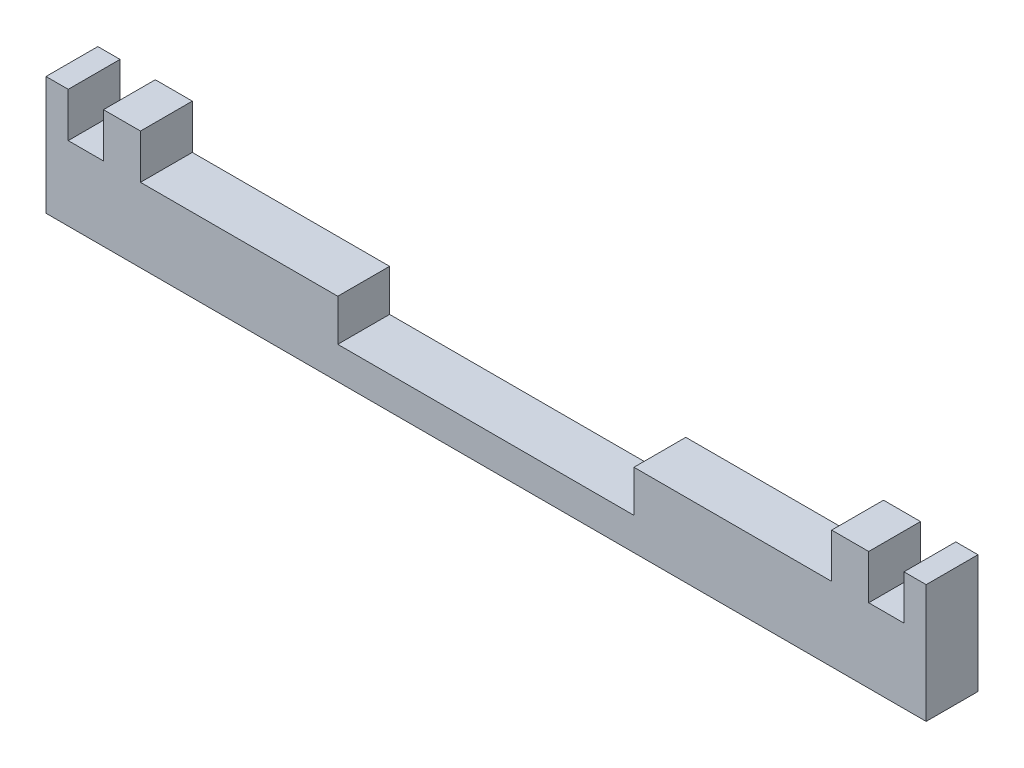
SolidWorks part; units mm, degrees
ref_plane "Front Plane" through (0, 0, 0) normal (0, 0, 1) x (1, 0, 0)
ref_plane "Top Plane" through (0, 0, 0) normal (0, 1, 0) x (1, 0, 0)
ref_plane "Right Plane" through (0, 0, 0) normal (1, 0, 0) x (0, 0, -1)
sketch "Sketch1" plane through (0, 0, 0) normal (0, 0, 1) x (1, 0, 0)
  line L8 (-95.4472, -23.6971) -> (55.505, -23.6971)
  line L9 (55.505, -23.6971) -> (55.505, -3.3771)
  line L10 (55.505, -3.3771) -> (51.695, -3.3771)
  line L11 (51.695, -3.3771) -> (51.695, -10.9971)
  line L12 (51.695, -10.9971) -> (45.6498, -10.9971)
  line L13 (45.6498, -10.9971) -> (45.6498, -3.3771)
  line L14 (45.6498, -3.3771) -> (39.2998, -3.3771)
  line L15 (39.2998, -3.3771) -> (39.2998, -10.9971)
  line L16 (39.2998, -10.9971) -> (-79.242, -10.9971)
  line L17 (-79.242, -10.9971) -> (-79.242, -3.3771)
  line L18 (-79.242, -3.3771) -> (-85.592, -3.3771)
  line L19 (-85.592, -3.3771) -> (-85.592, -10.9971)
  line L20 (-85.592, -10.9971) -> (-91.6372, -10.9971)
  line L21 (-91.6372, -10.9971) -> (-91.6372, -3.3771)
  line L22 (-91.6372, -3.3771) -> (-95.4472, -3.3771)
  line L23 (-95.4472, -3.3771) -> (-95.4472, -23.6971)
  point P2 (-88.6146, -10.9971)
  point P17 (48.6724, -10.9971)
  point P18 (0, 0)
  dimension "D1" = 137.287
  dimension "D2" = 6.0452
  dimension "D3" = 6.0452
  dimension "D4" = 7.62
  dimension "D5" = 6.35
  dimension "D6" = 7.62
  dimension "D7" = 7.62
  dimension "D8" = 7.62
  dimension "D9" = 3.81
  dimension "D10" = 3.81
  dimension "D11" = 6.35
  dimension "D12" = 12.7
extrude "Boss-Extrude1" add sketch "Sketch1" along normal blind 8.89
sketch "Sketch2" plane through (0, 0, 8.89) normal (0, 0, 1) x (1, 0, 0)
  line L0 (39.2998, -10.9971) -> (-79.242, -10.9971) construction
  line L1 (-45.4092, -10.9971) -> (5.3908, -10.9971)
  line L2 (-45.4092, -10.9971) -> (-45.4092, -18.1409)
  line L3 (-45.4092, -18.1409) -> (5.3908, -18.1409)
  line L4 (5.3908, -10.9971) -> (5.3908, -18.1409)
  line L5 (-95.4472, -3.3771) -> (-95.4472, -23.6971) construction
  point P6 (-20.0092, -10.9971)
  dimension "D1" = 7.1437
  dimension "D2" = 75.438
  dimension "D3" = 50.8
extrude "Cut-Extrude1" cut sketch "Sketch2" against normal blind 8.89
